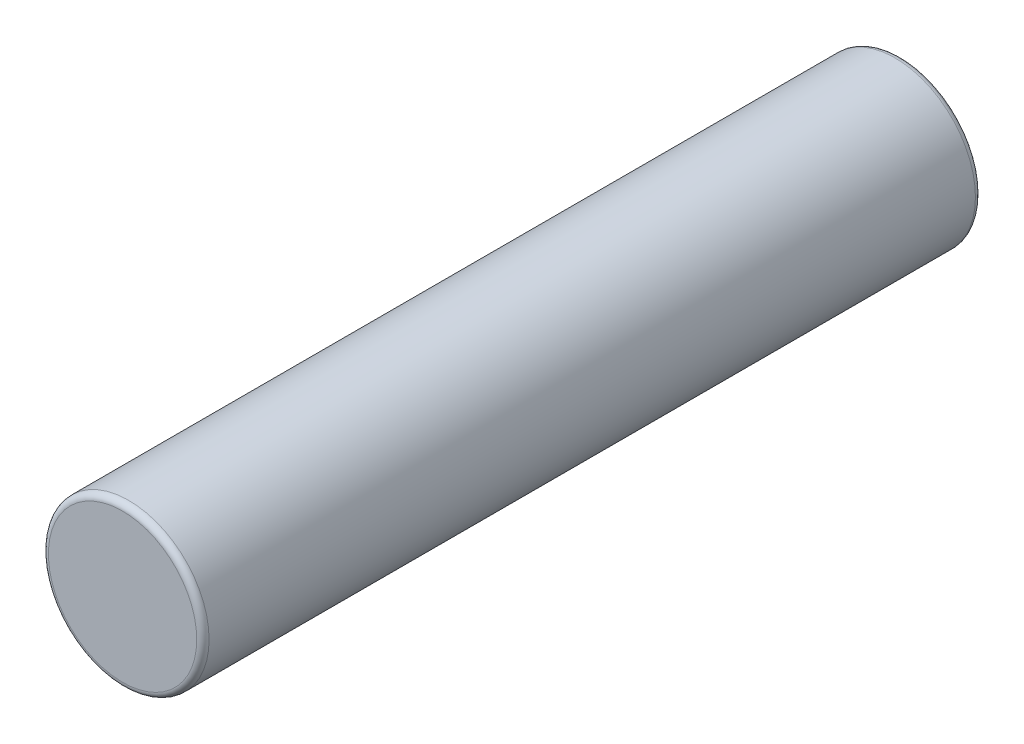
SolidWorks part; units mm, degrees
ref_plane "Płaszczyzna przednia" through (0, 0, 0) normal (0, 0, 1) x (1, 0, 0)
ref_plane "Płaszczyzna górna" through (0, 0, 0) normal (0, 1, 0) x (1, 0, 0)
ref_plane "Płaszczyzna prawa" through (0, 0, 0) normal (1, 0, 0) x (0, 0, -1)
sketch "Sketch1" plane through (0, 0, 0) normal (0, 0, 1) x (1, 0, 0)
  circle A0 centre (0, 0) radius 6.5
  dimension "D1" = 13
extrude "Boss-Extrude1" add sketch "Sketch1" along normal blind 63
fillet "Fillet1" radius 0.5 2 edges at (6.5, 0, 0) (6.5, 0, 63)
